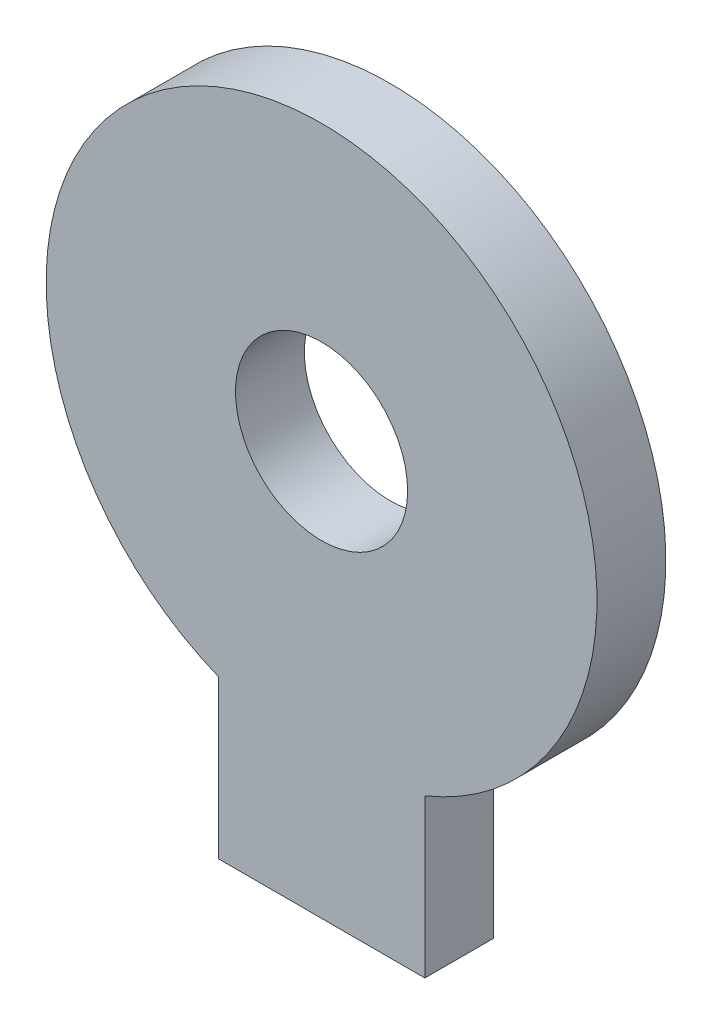
SolidWorks part; units mm, degrees
material "PW80:Mi:0:41:Ar:0:-1:C1:1:2:3:Re:15:"
ref_plane "Plan1" through (0, 0, 0) normal (0, 0, 1) x (1, 0, 0)
ref_plane "Plan2" through (0, 0, 0) normal (0, 1, 0) x (1, 0, 0)
ref_plane "Plan3" through (0, 0, 0) normal (1, 0, 0) x (0, 0, -1)
sketch "Esquisse1" plane through (0, 0, 0) normal (0, 0, 1) x (1, 0, 0)
  line L1 (0, 0) -> (6, 0)
  line L2 (0, 0) -> (0, 4.5838)
  line L4 (6, 0) -> (6, 4.5838)
  arc A0 (6, 4.5838) -> (0, 4.5838) centre (3, 12) ccw
extrude "Base-Extrusion" add sketch "Esquisse1" against normal blind 2
sketch "Esquisse2" plane through (0, 0, 0) normal (0, 0, 1) x (1, 0, 0)
  circle A0 centre (3, 12) radius 2.5
extrude "Enlèv. mat.-Extru.1" cut sketch "Esquisse2" against normal blind 2
